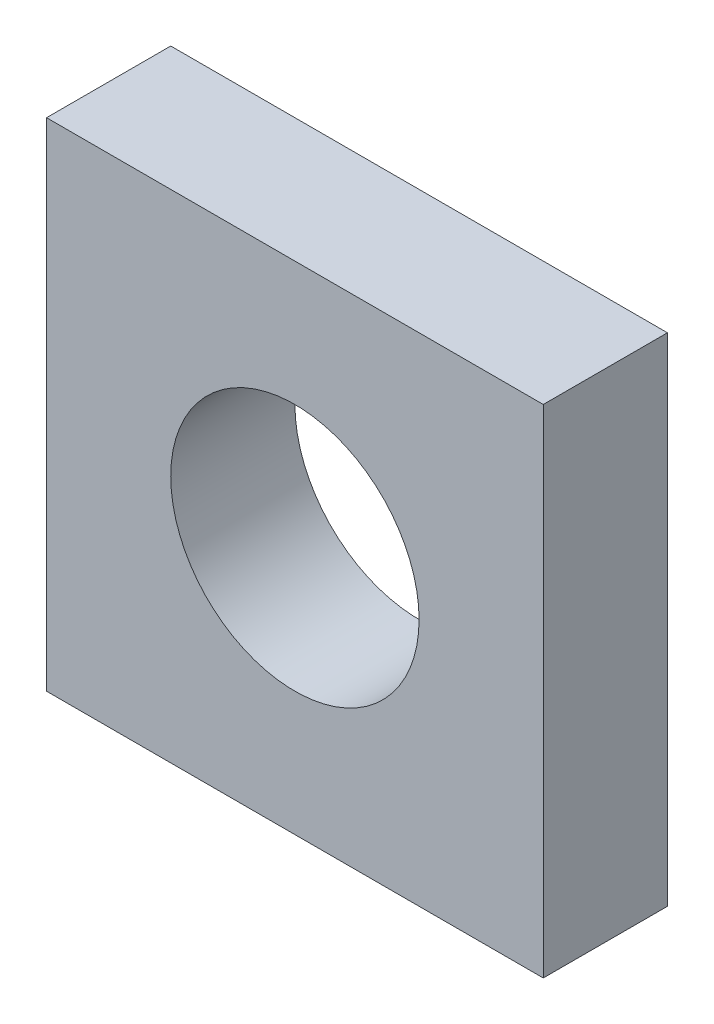
SolidWorks part; units mm, degrees
ref_plane "Plan de face" through (0, 0, 0) normal (0, 0, 1) x (1, 0, 0)
ref_plane "Plan de dessus" through (0, 0, 0) normal (0, 1, 0) x (1, 0, 0)
ref_plane "Plan de droite" through (0, 0, 0) normal (1, 0, 0) x (0, 0, -1)
sketch "Esquisse1" plane through (0, 0, 0) normal (0, 0, 1) x (1, 0, 0)
  line L1 (-0.6598, 0.7026) -> (1.3402, 0.7026)
  line L2 (-0.6598, 0.7026) -> (-0.6598, -1.2974)
  line L3 (-0.6598, -1.2974) -> (1.3402, -1.2974)
  line L4 (1.3402, 0.7026) -> (1.3402, -1.2974)
  circle A0 centre (0.3402, -0.2974) radius 0.5
  dimension "D3" = 1
  dimension "D1" = 2
  dimension "D2" = 2
extrude "Boss.-Extru.1" add sketch "Esquisse1" along normal blind 0.5
